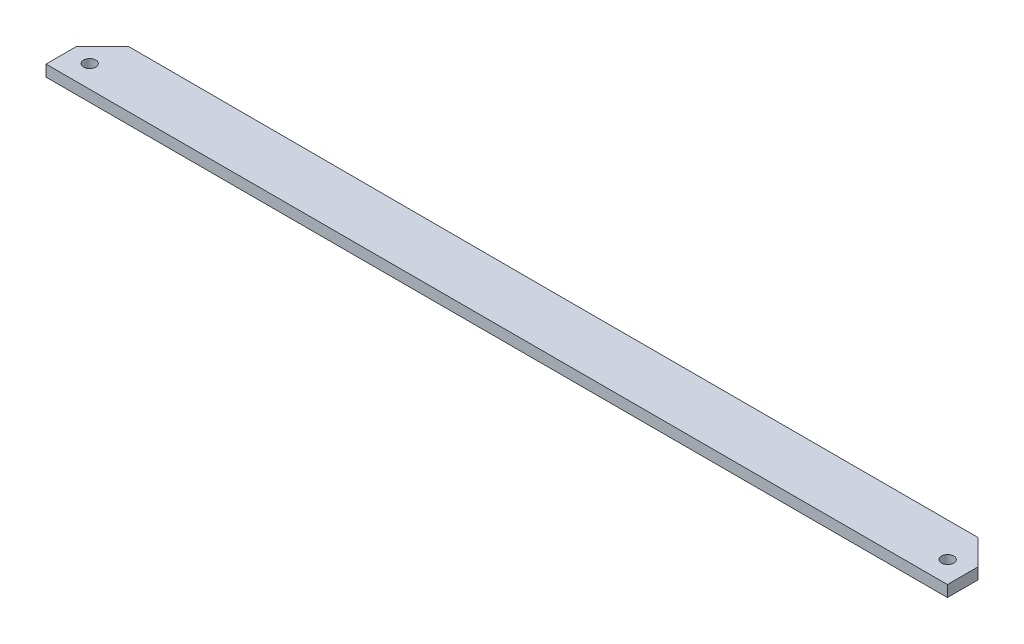
SolidWorks part; units mm, degrees
material "Acrylic (Medium-high impact)"
ref_plane "Front Plane" through (0, 0, 0) normal (0, 0, 1) x (1, 0, 0)
ref_plane "Top Plane" through (0, 0, 0) normal (0, 1, 0) x (1, 0, 0)
ref_plane "Right Plane" through (0, 0, 0) normal (1, 0, 0) x (0, 0, -1)
sketch "Sketch1" plane through (0, 0, 0) normal (0, 1, 0) x (1, 0, 0)
  line L0 (0, 0) -> (233.8665, 0)
  line L1 (233.8665, 0) -> (233.8665, 15.8702)
  line L2 (233.8665, 15.8702) -> (220.6625, 29.0741)
  line L3 (220.6625, 29.0741) -> (0, 29.0741)
  line L4 (0, 0) -> (-234.1327, 0)
  line L5 (-234.1327, 0) -> (-234.1327, 15.875)
  line L6 (-234.1327, 15.875) -> (-220.6623, 29.3454)
  line L7 (-220.6623, 29.3454) -> (0, 29.0741)
  point P3 (0, 0)
  point P10 (0, 0)
  point P11 (0, 0)
  point P12 (0, 0)
  point P13 (0, 0)
  point P14 (0, 0)
  point P15 (0, 0)
  point P16 (0, 0)
extrude "Boss-Extrude1" add sketch "Sketch1" along normal blind 5.8674
sketch "Sketch2" plane through (0, 0, 0) normal (0, -1, 0) x (1, 0, 0)
  line L0 (0, -29.0741) -> (-220.6623, -29.3454) construction
  line L1 (-234.1327, -15.875) -> (-234.1327, 0) construction
  circle A0 centre (-223.0202, -11.5683) radius 3.175
  dimension "D1" = 17.78
  dimension "D2" = 11.1125
extrude "Cut-Extrude2" cut sketch "Sketch2" against normal blind 10.16
sketch "Sketch4" plane through (0, 0, 0) normal (0, -1, 0) x (1, 0, 0)
  line L0 (220.6625, -29.0741) -> (0, -29.0741) construction
  line L1 (233.8665, 0) -> (233.8665, -15.8702) construction
  circle A0 centre (222.6905, -11.2941) radius 3.175
  dimension "D1" = 17.78
  dimension "D2" = 11.176
extrude "Cut-Extrude3" cut sketch "Sketch4" against normal blind 10.16
